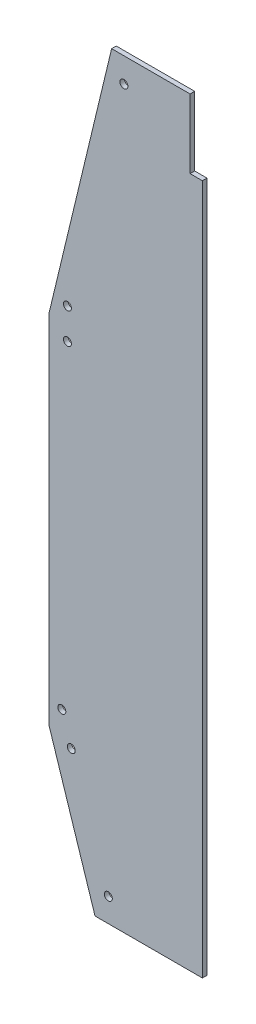
SolidWorks part; units mm, degrees
ref_plane "Plan de face" through (0, 0, 0) normal (0, 0, 1) x (1, 0, 0)
ref_plane "Plan de dessus" through (0, 0, 0) normal (0, 1, 0) x (1, 0, 0)
ref_plane "Plan de droite" through (0, 0, 0) normal (1, 0, 0) x (0, 0, -1)
sketch "Esquisse1" plane through (0, 0, 0) normal (0, 0, 1) x (1, 0, 0)
  line L0 (0, 450.3) -> (-8, 450.3)
  line L1 (0, 0) -> (-70, 0)
  line L2 (0, 0) -> (0, 450.3)
  line L3 (-8, 495.3) -> (-59.18, 495.3)
  line L4 (-100, 92.65) -> (-100, 325.5)
  line L5 (-8, 450.3) -> (-8, 495.3)
  line L6 (-59.18, 495.3) -> (-100, 325.5)
  line L8 (-70, 0) -> (-100, 92.65)
  dimension "D1" = 100
  dimension "D2" = 495.3
  dimension "D3" = 8
  dimension "D4" = 45
  dimension "D5" = 51.18
  dimension "D6" = 169.8
  dimension "D7" = 92.65
  dimension "D8" = 70
extrude "Boss.-Extru.1" add sketch "Esquisse1" along normal blind 3
sketch "Esquisse2" plane through (0, 0, 0) normal (0, 0, -1) x (-1, 0, 0)
  circle A0 centre (61.3352, 15.4407) radius 2.6 construction
  circle A1 centre (85.503, 86.8329) radius 2.6 construction
  circle A2 centre (91.6641, 105.8603) radius 2.6 construction
  circle A3 centre (88, 315.5) radius 2.6 construction
  circle A4 centre (88, 335.5) radius 2.6 construction
  circle A5 centre (51.1658, 479.3) radius 2.6 construction
  circle A6 centre (61.3352, 15.4407) radius 2.6
  circle A7 centre (85.503, 86.8329) radius 2.6
  circle A8 centre (91.6641, 105.8603) radius 2.6
  circle A9 centre (88, 315.5) radius 2.6
  circle A10 centre (88, 335.5) radius 2.6
  circle A11 centre (51.1658, 479.3) radius 2.6
extrude "Enlèv. mat.-Extru.1" cut sketch "Esquisse2" against normal blind 20
